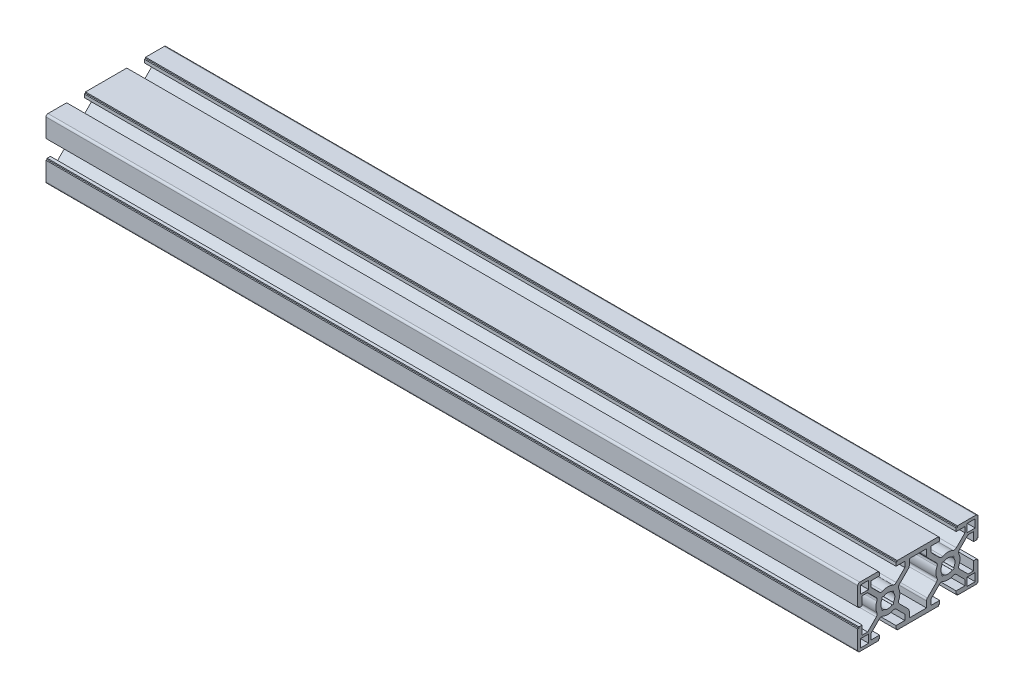
SolidWorks part; units mm, degrees
ref_plane "Front Plane" through (0, 0, 0) normal (0, 0, 1) x (1, 0, 0)
ref_plane "Top Plane" through (0, 0, 0) normal (0, 1, 0) x (1, 0, 0)
ref_plane "Right Plane" through (0, 0, 0) normal (1, 0, 0) x (0, 0, -1)
ref_plane "Plane1" through (405, 0, 0) normal (1, 0, 0) x (0, 0, -1)
sketch "Sketch1" plane through (405, 0, 0) normal (1, 0, 0) x (0, 0, -1)
  line L0 (-10.8034, -20.7523) -> (-6.5, -25.0556)
  line L1 (-6.5, -25.0556) -> (-6.5, -27.8)
  line L2 (-6.5, -27.8) -> (-10.9, -27.8)
  line L3 (-10.9, -27.8) -> (-10.9, -29.4)
  line L4 (-10.9, -29.4) -> (-10.3, -29.4)
  line L5 (-10.3, -29.4) -> (-10.3, -30)
  line L6 (-10.3, -30) -> (-1, -30)
  line L7 (0, -29) -> (0, -19.7)
  line L8 (0, -19.7) -> (-0.6, -19.7)
  line L9 (-0.6, -19.7) -> (-0.6, -19.1)
  line L10 (-0.6, -19.1) -> (-2.2, -19.1)
  line L11 (-2.2, -19.1) -> (-2.2, -23.5)
  line L12 (-2.2, -23.5) -> (-4.9444, -23.5)
  line L13 (-4.9444, -23.5) -> (-9.2477, -19.1966)
  line L14 (-9.2477, -10.8034) -> (-4.9444, -6.5)
  line L15 (-4.9444, -6.5) -> (-2.2, -6.5)
  line L16 (-2.2, -6.5) -> (-2.2, -10.9)
  line L17 (-2.2, -10.9) -> (-0.6, -10.9)
  line L18 (-0.6, -10.9) -> (-0.6, -10.3)
  line L19 (-0.6, -10.3) -> (0, -10.3)
  line L20 (0, -10.3) -> (0, -1)
  line L21 (-1, 0) -> (-10.3, 0)
  line L22 (-10.3, 0) -> (-10.3, -0.6)
  line L23 (-10.3, -0.6) -> (-10.9, -0.6)
  line L24 (-10.9, -0.6) -> (-10.9, -2.2)
  line L25 (-10.9, -2.2) -> (-6.5, -2.2)
  line L26 (-6.5, -2.2) -> (-6.5, -4.9444)
  line L27 (-6.5, -4.9444) -> (-10.8034, -9.2477)
  line L28 (-19.1966, -9.2477) -> (-23.5, -4.9444)
  line L29 (-23.5, -4.9444) -> (-23.5, -2.2)
  line L30 (-23.5, -2.2) -> (-19.1, -2.2)
  line L31 (-19.1, -2.2) -> (-19.1, -0.6)
  line L32 (-19.1, -0.6) -> (-19.7, -0.6)
  line L33 (-19.7, -0.6) -> (-19.7, 0)
  line L34 (-19.7, 0) -> (-40.3, 0)
  line L35 (-40.3, 0) -> (-40.3, -0.6)
  line L36 (-40.3, -0.6) -> (-40.9, -0.6)
  line L37 (-40.9, -0.6) -> (-40.9, -2.2)
  line L38 (-40.9, -2.2) -> (-36.5, -2.2)
  line L39 (-36.5, -2.2) -> (-36.5, -4.9444)
  line L40 (-36.5, -4.9444) -> (-40.8034, -9.2477)
  line L41 (-49.1966, -9.2477) -> (-53.5, -4.9444)
  line L42 (-53.5, -4.9444) -> (-53.5, -2.2)
  line L43 (-53.5, -2.2) -> (-49.1, -2.2)
  line L44 (-49.1, -2.2) -> (-49.1, -0.6)
  line L45 (-49.1, -0.6) -> (-49.7, -0.6)
  line L46 (-49.7, -0.6) -> (-49.7, 0)
  line L47 (-49.7, 0) -> (-59, 0)
  line L48 (-60, -1) -> (-60, -10.3)
  line L49 (-60, -10.3) -> (-59.4, -10.3)
  line L50 (-59.4, -10.3) -> (-59.4, -10.9)
  line L51 (-59.4, -10.9) -> (-57.8, -10.9)
  line L52 (-57.8, -10.9) -> (-57.8, -6.5)
  line L53 (-57.8, -6.5) -> (-55.0556, -6.5)
  line L54 (-55.0556, -6.5) -> (-50.7523, -10.8034)
  line L55 (-50.7523, -19.1966) -> (-55.0556, -23.5)
  line L56 (-55.0556, -23.5) -> (-57.8, -23.5)
  line L57 (-57.8, -23.5) -> (-57.8, -19.1)
  line L58 (-57.8, -19.1) -> (-59.4, -19.1)
  line L59 (-59.4, -19.1) -> (-59.4, -19.7)
  line L60 (-59.4, -19.7) -> (-60, -19.7)
  line L61 (-60, -19.7) -> (-60, -29)
  line L62 (-59, -30) -> (-49.7, -30)
  line L63 (-49.7, -30) -> (-49.7, -29.4)
  line L64 (-49.7, -29.4) -> (-49.1, -29.4)
  line L65 (-49.1, -29.4) -> (-49.1, -27.8)
  line L66 (-49.1, -27.8) -> (-53.5, -27.8)
  line L67 (-53.5, -27.8) -> (-53.5, -25.0556)
  line L68 (-53.5, -25.0556) -> (-49.1966, -20.7523)
  line L69 (-40.8034, -20.7523) -> (-36.5, -25.0556)
  line L70 (-36.5, -25.0556) -> (-36.5, -27.8)
  line L71 (-36.5, -27.8) -> (-40.9, -27.8)
  line L72 (-40.9, -27.8) -> (-40.9, -29.4)
  line L73 (-40.9, -29.4) -> (-40.3, -29.4)
  line L74 (-40.3, -29.4) -> (-40.3, -30)
  line L75 (-40.3, -30) -> (-19.7, -30)
  line L76 (-19.7, -30) -> (-19.7, -29.4)
  line L77 (-19.7, -29.4) -> (-19.1, -29.4)
  line L78 (-19.1, -29.4) -> (-19.1, -27.8)
  line L79 (-19.1, -27.8) -> (-23.5, -27.8)
  line L80 (-23.5, -27.8) -> (-23.5, -25.0556)
  line L81 (-23.5, -25.0556) -> (-19.1966, -20.7523)
  line L82 (-54.6, -28.6) -> (-58.6, -28.6)
  line L83 (-58.6, -28.6) -> (-58.6, -24.6)
  line L84 (-58.6, -24.6) -> (-54.6, -24.6)
  line L85 (-54.6, -24.6) -> (-54.6, -28.6)
  line L86 (-54.6, -1.4) -> (-54.6, -5.4)
  line L87 (-54.6, -5.4) -> (-58.6, -5.4)
  line L88 (-58.6, -5.4) -> (-58.6, -1.4)
  line L89 (-58.6, -1.4) -> (-54.6, -1.4)
  line L90 (-5.4, -28.6) -> (-5.4, -24.6)
  line L91 (-5.4, -24.6) -> (-1.4, -24.6)
  line L92 (-1.4, -24.6) -> (-1.4, -28.6)
  line L93 (-1.4, -28.6) -> (-5.4, -28.6)
  line L94 (-5.4, -1.4) -> (-1.4, -1.4)
  line L95 (-1.4, -1.4) -> (-1.4, -5.4)
  line L96 (-1.4, -5.4) -> (-5.4, -5.4)
  line L97 (-5.4, -5.4) -> (-5.4, -1.4)
  line L98 (-39.2477, -10.8034) -> (-34.7393, -6.295)
  line L99 (-34.3, -5.2343) -> (-34.3, -2.2)
  line L100 (-34.3, -2.2) -> (-25.7, -2.2)
  line L101 (-25.7, -2.2) -> (-25.7, -5.2343)
  line L102 (-25.2607, -6.295) -> (-20.7523, -10.8034)
  line L103 (-20.7523, -19.1966) -> (-25.2607, -23.705)
  line L104 (-25.7, -24.7657) -> (-25.7, -27.8)
  line L105 (-25.7, -27.8) -> (-34.3, -27.8)
  line L106 (-34.3, -27.8) -> (-34.3, -24.7657)
  line L107 (-34.7393, -23.705) -> (-39.2477, -19.1966)
  arc A0 (-19.1966, -20.7523) -> (-17.5088, -20.4503) centre (-18.136, -21.8129) cw
  arc A1 (-17.5088, -20.4503) -> (-12.4912, -20.4503) centre (-15, -15) ccw
  arc A2 (-12.4912, -20.4503) -> (-10.8034, -20.7523) centre (-11.864, -21.8129) cw
  arc A3 (-1, -30) -> (0, -29) centre (-1, -29) ccw
  arc A4 (-9.2477, -19.1966) -> (-9.5497, -17.5088) centre (-8.1871, -18.136) cw
  arc A5 (-9.5497, -17.5088) -> (-9.5497, -12.4912) centre (-15, -15) ccw
  arc A6 (-9.5497, -12.4912) -> (-9.2477, -10.8034) centre (-8.1871, -11.864) cw
  arc A7 (0, -1) -> (-1, 0) centre (-1, -1) ccw
  arc A8 (-10.8034, -9.2477) -> (-12.4912, -9.5497) centre (-11.864, -8.1871) cw
  arc A9 (-12.4912, -9.5497) -> (-17.5088, -9.5497) centre (-15, -15) ccw
  arc A10 (-17.5088, -9.5497) -> (-19.1966, -9.2477) centre (-18.136, -8.1871) cw
  arc A11 (-40.8034, -9.2477) -> (-42.4912, -9.5497) centre (-41.864, -8.1871) cw
  arc A12 (-42.4912, -9.5497) -> (-47.5088, -9.5497) centre (-45, -15) ccw
  arc A13 (-47.5088, -9.5497) -> (-49.1966, -9.2477) centre (-48.136, -8.1871) cw
  arc A14 (-59, 0) -> (-60, -1) centre (-59, -1) ccw
  arc A15 (-50.7523, -10.8034) -> (-50.4503, -12.4912) centre (-51.8129, -11.864) cw
  arc A16 (-50.4503, -12.4912) -> (-50.4503, -17.5088) centre (-45, -15) ccw
  arc A17 (-50.4503, -17.5088) -> (-50.7523, -19.1966) centre (-51.8129, -18.136) cw
  arc A18 (-60, -29) -> (-59, -30) centre (-59, -29) ccw
  arc A19 (-49.1966, -20.7523) -> (-47.5088, -20.4503) centre (-48.136, -21.8129) cw
  arc A20 (-47.5088, -20.4503) -> (-42.4912, -20.4503) centre (-45, -15) ccw
  arc A21 (-42.4912, -20.4503) -> (-40.8034, -20.7523) centre (-41.864, -21.8129) cw
  arc A22 (-47.8023, -17.097) -> (-47.8023, -12.903) centre (-45, -15) cw
  arc A23 (-47.8023, -12.903) -> (-47.097, -12.1977) centre (-47.4749, -12.5251) cw
  arc A24 (-47.097, -12.1977) -> (-42.903, -12.1977) centre (-45, -15) cw
  arc A25 (-42.903, -12.1977) -> (-42.1977, -12.903) centre (-42.5251, -12.5251) cw
  arc A26 (-42.1977, -12.903) -> (-42.1977, -17.097) centre (-45, -15) cw
  arc A27 (-42.1977, -17.097) -> (-42.903, -17.8023) centre (-42.5251, -17.4749) cw
  arc A28 (-42.903, -17.8023) -> (-47.097, -17.8023) centre (-45, -15) cw
  arc A29 (-47.097, -17.8023) -> (-47.8023, -17.097) centre (-47.4749, -17.4749) cw
  arc A30 (-12.1977, -12.903) -> (-12.1977, -17.097) centre (-15, -15) cw
  arc A31 (-12.1977, -17.097) -> (-12.903, -17.8023) centre (-12.5251, -17.4749) cw
  arc A32 (-12.903, -17.8023) -> (-17.097, -17.8023) centre (-15, -15) cw
  arc A33 (-17.097, -17.8023) -> (-17.8023, -17.097) centre (-17.4749, -17.4749) cw
  arc A34 (-17.8023, -17.097) -> (-17.8023, -12.903) centre (-15, -15) cw
  arc A35 (-17.8023, -12.903) -> (-17.097, -12.1977) centre (-17.4749, -12.5251) cw
  arc A36 (-17.097, -12.1977) -> (-12.903, -12.1977) centre (-15, -15) cw
  arc A37 (-12.903, -12.1977) -> (-12.1977, -12.903) centre (-12.5251, -12.5251) cw
  arc A38 (-34.7393, -6.295) -> (-34.3, -5.2343) centre (-35.8, -5.2343) ccw
  arc A39 (-25.7, -5.2343) -> (-25.2607, -6.295) centre (-24.2, -5.2343) ccw
  arc A40 (-20.7523, -10.8034) -> (-20.4503, -12.4912) centre (-21.8129, -11.864) cw
  arc A41 (-20.4503, -12.4912) -> (-20.4503, -17.5088) centre (-15, -15) ccw
  arc A42 (-20.4503, -17.5088) -> (-20.7523, -19.1966) centre (-21.8129, -18.136) cw
  arc A43 (-25.2607, -23.705) -> (-25.7, -24.7657) centre (-24.2, -24.7657) ccw
  arc A44 (-34.3, -24.7657) -> (-34.7393, -23.705) centre (-35.8, -24.7657) ccw
  arc A45 (-39.2477, -19.1966) -> (-39.5497, -17.5088) centre (-38.1871, -18.136) cw
  arc A46 (-39.5497, -17.5088) -> (-39.5497, -12.4912) centre (-45, -15) ccw
  arc A47 (-39.5497, -12.4912) -> (-39.2477, -10.8034) centre (-38.1871, -11.864) cw
extrude "Boss-Extrude1" add sketch "Sketch1" against normal blind 405
